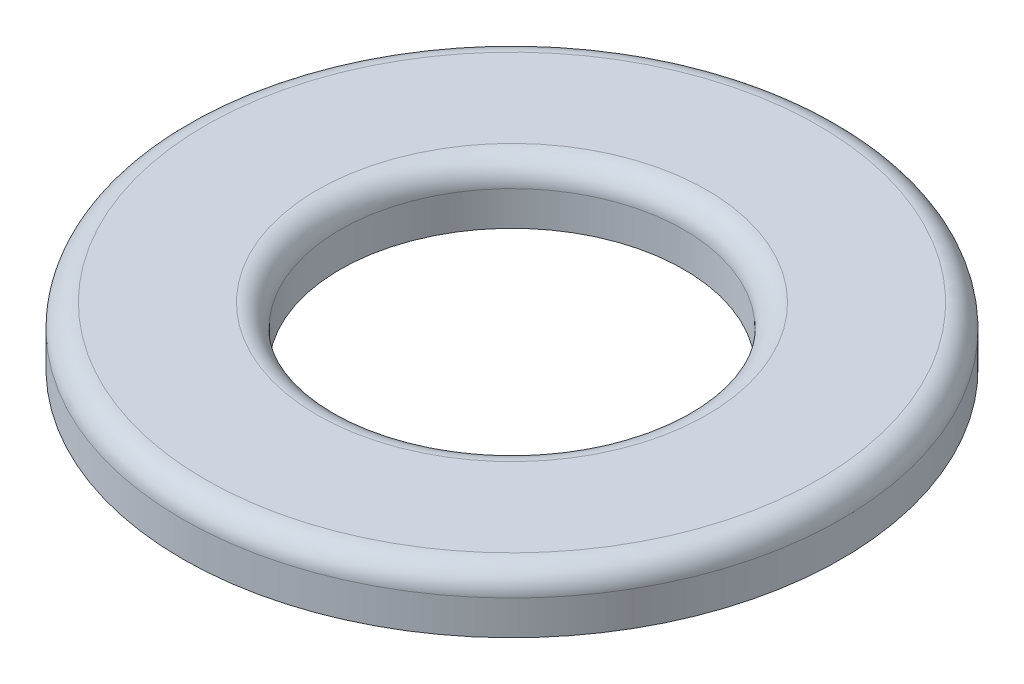
SolidWorks part; units mm, degrees
material "1060 Alloy"
ref_plane "Front Plane" through (0, 0, 0) normal (0, 0, 1) x (1, 0, 0)
ref_plane "Top Plane" through (0, 0, 0) normal (0, 1, 0) x (1, 0, 0)
ref_plane "Right Plane" through (0, 0, 0) normal (1, 0, 0) x (0, 0, -1)
sketch "Sketch1" plane through (0, 0, 0) normal (0, 1, 0) x (1, 0, 0)
  circle A0 centre (0, 0) radius 2.875
  circle A1 centre (0, 0) radius 1.5
  dimension "D1" = 5.75
  dimension "D2" = 3
extrude "Boss-Extrude1" add sketch "Sketch1" along normal blind 0.5
fillet "Fillet1" radius 0.2 2 edges at (0, 0.5, 1.5) (0, 0.5, 2.875)
